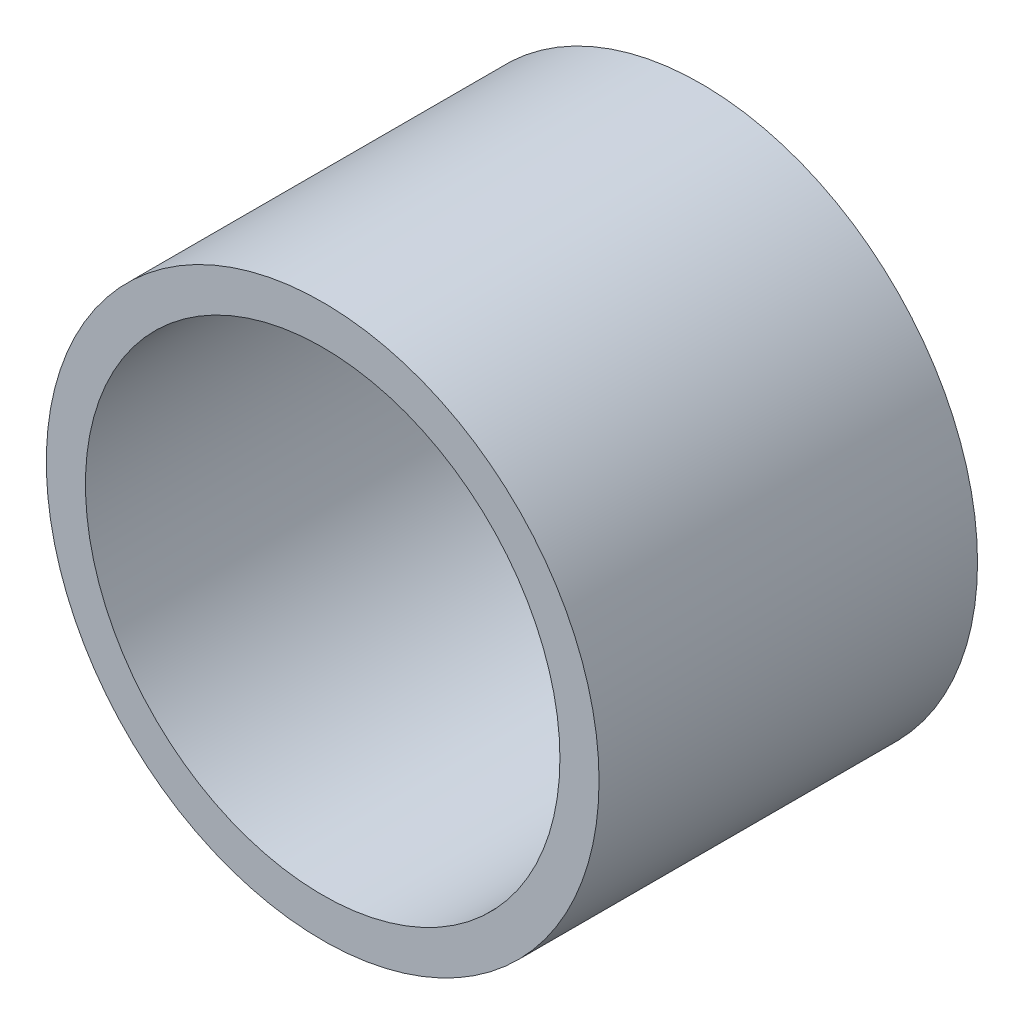
SolidWorks part; units mm, degrees
material "PVC Rigid"
ref_plane "Front Plane" through (0, 0, 0) normal (0, 0, 1) x (1, 0, 0)
ref_plane "Top Plane" through (0, 0, 0) normal (0, 1, 0) x (1, 0, 0)
ref_plane "Right Plane" through (0, 0, 0) normal (1, 0, 0) x (0, 0, -1)
sketch "Sketch1" plane through (0, 0, 0) normal (0, 0, 1) x (1, 0, 0)
  circle A0 centre (0, 0) radius 31.3436
  circle A1 centre (0, 0) radius 36.5125
  dimension "D1" = 73.025
  dimension "D2" = 62.6872
extrude "Boss-Extrude1" add sketch "Sketch1" along normal blind 50
